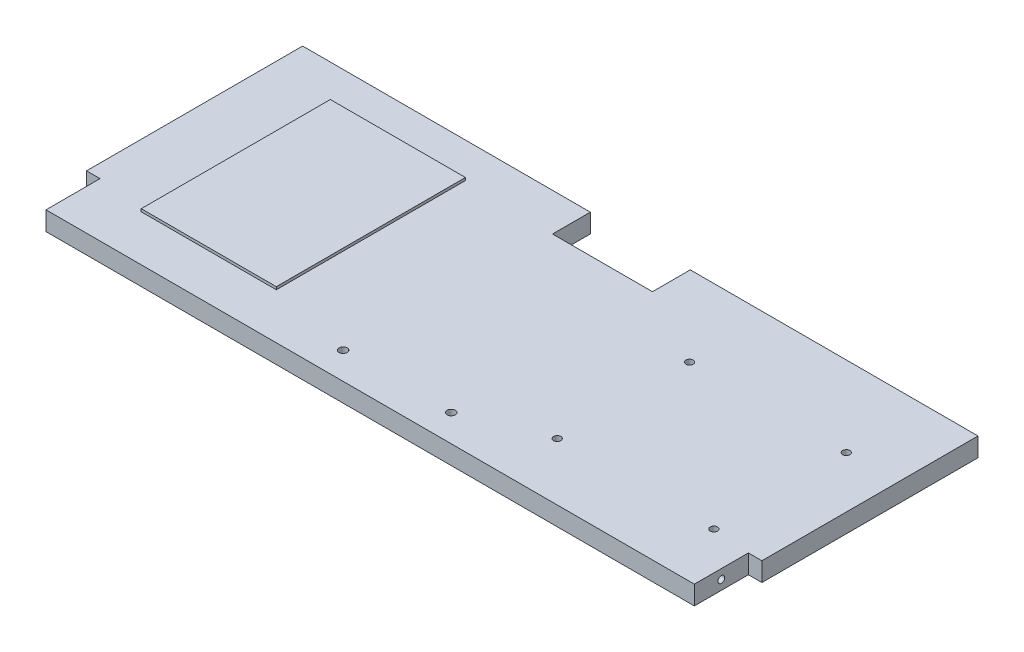
SolidWorks part; units mm, degrees
ref_plane "Ebene vorne" through (0, 0, 0) normal (0, 0, 1) x (1, 0, 0)
ref_plane "Ebene oben" through (0, 0, 0) normal (0, 1, 0) x (1, 0, 0)
ref_plane "Ebene rechts" through (0, 0, 0) normal (1, 0, 0) x (0, 0, -1)
sketch "Skizze1" plane through (0, 0, 0) normal (0, 1, 0) x (1, 0, 0)
  line L1 (-125, -125) -> (125, -125)
  line L2 (-125, -125) -> (-125, 125)
  line L3 (-125, 125) -> (125, 125)
  line L4 (125, -125) -> (125, 125)
  line L5 (-125, -125) -> (125, 125) construction
  line L6 (-125, 125) -> (125, -125) construction
  point P0 (0, 0)
  dimension "D1" = 250
  dimension "D2" = 250
extrude "Aufsatz-Linear austragen1" add sketch "Skizze1" along normal blind 5
sketch "Skizze2" plane through (0, 5, 0) normal (0, 1, 0) x (1, 0, 0)
  line L1 (-112.1275, -114.481) -> (-66.1275, -114.481)
  line L2 (-112.1275, -114.481) -> (-112.1275, -3.481)
  line L3 (-112.1275, -3.481) -> (-66.1275, -3.481)
  line L4 (-66.1275, -114.481) -> (-66.1275, -3.481)
  line L5 (-108.0153, 50.9925) -> (-23.0153, 50.9925)
  line L6 (-108.0153, 50.9925) -> (-108.0153, 110.9925)
  line L7 (-108.0153, 110.9925) -> (-23.0153, 110.9925)
  line L8 (-23.0153, 50.9925) -> (-23.0153, 110.9925)
  line L9 (-20, -105) -> (20, -105)
  line L10 (-20, -105) -> (-20, -65)
  line L11 (-20, -65) -> (20, -65)
  line L12 (20, -105) -> (20, -65)
  line L13 (65, -20) -> (105, -20)
  line L14 (65, -20) -> (65, 20)
  line L15 (65, 20) -> (105, 20)
  line L16 (105, -20) -> (105, 20)
  line L17 (6.7738, 50.9925) -> (91.7738, 50.9925)
  line L18 (6.7738, 50.9925) -> (6.7738, 110.9925)
  line L19 (6.7738, 110.9925) -> (91.7738, 110.9925)
  line L20 (91.7738, 50.9925) -> (91.7738, 110.9925)
  line L21 (-125, 125) -> (-125, -125) construction
  line L22 (-125, -125) -> (125, -125) construction
  line L23 (-100.1275, -122.481) -> (-100.1275, 4.519)
  line L24 (-120.1275, -122.481) -> (-58.1275, -122.481)
  line L25 (-120.1275, -122.481) -> (-120.1275, 4.519)
  line L26 (-120.1275, 4.519) -> (-58.1275, 4.519)
  line L27 (-58.1275, -122.481) -> (-58.1275, 4.519)
  line L28 (-78.1275, -122.481) -> (-78.1275, 4.519)
  line L29 (-120.1275, -92.481) -> (-57.4038, -92.481)
  line L30 (-120.1275, -25.481) -> (-58.1275, -25.481)
  circle A0 centre (0, 0) radius 1.65
  dimension "D1" = 3.3
  dimension "D2" = 46
  dimension "D3" = 111
  dimension "D4" = 40
  dimension "D5" = 40
  dimension "D6" = 60
  dimension "D7" = 85
  dimension "D8" = 40
  dimension "D9" = 40
  dimension "D10" = 65
  dimension "D11" = 125
  dimension "D12" = 125
  dimension "D13" = 65
  dimension "D14" = 105
  dimension "D15" = 105
  dimension "D16" = 8
  dimension "D17" = 8
  dimension "D18" = 8
  dimension "D19" = 8
  dimension "D20" = 30
  dimension "D21" = 30
  dimension "D22" = 20
  dimension "D23" = 20
extrude "Aufsatz-Linear austragen2" add sketch "Skizze2" along normal blind 15 contours L29 L25 L24 L23 L1 L2 | L29 L4 L1 L28 L24 L27 | L4 L30 L27 L26 L28 L3 | L25 L30 L2 L3 L23 L26 | L9 L12 L11 L10 | L13 L16 L15 L14
sketch "Skizze3" plane through (0, 20, 0) normal (0, 1, 0) x (1, 0, 0)
  line L0 (65, -20) -> (65, 20) construction
  line L1 (-20, -105) -> (20, -105)
  line L2 (-20, -105) -> (-20, -65)
  line L3 (-20, -65) -> (20, -65)
  line L4 (20, -105) -> (20, -65)
  line L5 (65, -20) -> (105, -20)
  line L6 (65, -20) -> (65, 20)
  line L7 (65, 20) -> (105, 20)
  line L8 (105, -20) -> (105, 20)
  line L9 (70, -15) -> (100, -15)
  line L10 (70, -15) -> (70, 15)
  line L11 (70, 15) -> (100, 15)
  line L12 (100, -15) -> (100, 15)
  line L13 (-15, -100) -> (15, -100)
  line L14 (-15, -100) -> (-15, -70)
  line L15 (-15, -70) -> (15, -70)
  line L16 (15, -100) -> (15, -70)
  circle A0 centre (0, 0) radius 1.65
  dimension "D9" = 3.3
  dimension "D1" = 5
  dimension "D2" = 5
  dimension "D3" = 5
  dimension "D4" = 5
  dimension "D5" = 5
  dimension "D6" = 5
  dimension "D7" = 5
  dimension "D8" = 5
extrude "Schnitt-Linear austragen1" cut sketch "Skizze3" against normal blind 15 contours L14 L13 L16 L15 | L10 L9 L12 L11 | A0
sketch "Skizze4" plane through (0, 5, 0) normal (0, 1, 0) x (1, 0, 0)
  line L1 (-15, -100) -> (15, -100)
  line L2 (-15, -100) -> (-15, -70)
  line L3 (-15, -70) -> (15, -70)
  line L4 (15, -100) -> (15, -70)
  line L5 (70, -15) -> (100, -15)
  line L6 (70, -15) -> (70, 15)
  line L7 (70, 15) -> (100, 15)
  line L8 (100, -15) -> (100, 15)
  circle A0 centre (0, 0) radius 1.65
  dimension "D1" = 3.3
extrude "Schnitt-Linear austragen2" cut sketch "Skizze4" against normal blind 15
sketch "Skizze6" plane through (0, 20, 0) normal (0, 1, 0) x (1, 0, 0)
  line L1 (-20, -105) -> (20, -105)
  line L2 (-20, -105) -> (-20, -65)
  line L3 (-20, -65) -> (20, -65)
  line L4 (20, -105) -> (20, -65)
  line L5 (65, -20) -> (105, -20)
  line L6 (65, -20) -> (65, 20)
  line L7 (65, 20) -> (105, 20)
  line L8 (105, -20) -> (105, 20)
extrude "Aufsatz-Linear austragen3" add sketch "Skizze6" against normal blind 5
sketch "Skizze7" plane through (0, 5, 0) normal (0, 1, 0) x (1, 0, 0)
  line L12 (-20, -105) -> (20, -105)
  line L13 (-20, -105) -> (-20, -65)
  line L14 (-20, -65) -> (20, -65)
  line L15 (20, -105) -> (20, -65)
  line L16 (65, -20) -> (105, -20)
  line L17 (65, -20) -> (65, 20)
  line L18 (65, 20) -> (105, 20)
  line L19 (105, -20) -> (105, 20)
extrude "Schnitt-Linear austragen3" cut sketch "Skizze7" along normal blind 43
sketch "Skizze8" plane through (0, 5, 0) normal (0, 1, 0) x (1, 0, 0)
  line L1 (-15, -100) -> (15, -100)
  line L2 (-15, -100) -> (-15, -70)
  line L3 (-15, -70) -> (15, -70)
  line L4 (15, -100) -> (15, -70)
  line L5 (70, -15) -> (100, -15)
  line L6 (70, -15) -> (70, 15)
  line L7 (70, 15) -> (100, 15)
  line L8 (100, -15) -> (100, 15)
extrude "Aufsatz-Linear austragen4" add sketch "Skizze8" against normal blind 5
sketch "Skizze9" plane through (0, 5, 0) normal (0, 1, 0) x (1, 0, 0)
  line L0 (0, -71) -> (0, -34.8212)
  line L1 (-6, -116) -> (39, -116)
  line L2 (-6, -116) -> (-6, -71)
  line L3 (-6, -71) -> (39, -71)
  line L4 (39, -116) -> (39, -71)
  line L5 (71, -39) -> (116, -39)
  line L6 (71, -39) -> (71, 6)
  line L7 (71, 6) -> (116, 6)
  line L8 (116, -39) -> (116, 6)
  line L9 (71, 0) -> (36.9303, 0)
  line L10 (125, 125) -> (-125, 125) construction
  line L11 (125, -125) -> (125, 125) construction
  dimension "D1" = 45
  dimension "D2" = 45
  dimension "D3" = 45
  dimension "D4" = 45
  dimension "D5" = 71
  dimension "D6" = 71
  dimension "D7" = 6
  dimension "D8" = 6
  dimension "D9" = 125
  dimension "D10" = 125
extrude "Aufsatz-Linear austragen5" add sketch "Skizze9" along normal blind 15 contours L1 L4 L3 L2 | L5 L8 L7 L6
sketch "Skizze10" plane through (0, 5, 0) normal (0, 1, 0) x (1, 0, 0)
  line L0 (-6, -116) -> (-6, -71) construction
  line L1 (-6, -93) -> (-14, -93)
  line L2 (-6, -93) -> (-6, -85)
  line L3 (-6, -85) -> (-14, -85)
  line L4 (-14, -93) -> (-14, -85)
  line L5 (39, -116) -> (39, -71) construction
  line L6 (39, -93) -> (47, -93)
  line L7 (39, -93) -> (39, -85)
  line L8 (39, -85) -> (47, -85)
  line L9 (47, -93) -> (47, -85)
  line L15 (71, 6) -> (116, 6) construction
  line L16 (93, 6) -> (85, 6)
  line L17 (93, 6) -> (93, 14)
  line L18 (93, 14) -> (85, 14)
  line L19 (85, 6) -> (85, 14)
  line L22 (71, -39) -> (71, 6) construction
  line L23 (85, -39) -> (93, -39)
  line L24 (85, -39) -> (85, -47)
  line L25 (85, -47) -> (93, -47)
  line L26 (93, -39) -> (93, -47)
  line L27 (-6, -71) -> (39, -71) construction
  line L28 (-6, -71) -> (39, -71) construction
  dimension "D1" = 8
  dimension "D2" = 8
  dimension "D3" = 14
  dimension "D4" = 8
  dimension "D5" = 8
  dimension "D7" = 8
  dimension "D8" = 14
  dimension "D9" = 8
  dimension "D10" = 14
  dimension "D11" = 14
  dimension "D12" = 8
  dimension "D13" = 8
extrude "Aufsatz-Linear austragen6" add sketch "Skizze10" along normal blind 34 contours L7 L6 L9 L8 | L2 L1 L4 L3 | L24 L23 L26 L25 | L17 L16 L19 L18
sketch "Skizze11" plane through (0, 0, 85) normal (0, 0, -1) x (-1, 0, 0)
  line L0 (-47, 39) -> (-47, 5) construction
  line L1 (14, 39) -> (6, 39)
  line L2 (14, 39) -> (14, 20)
  line L3 (14, 20) -> (6, 20)
  line L4 (6, 39) -> (6, 20)
  line L5 (-39, 39) -> (-47, 39)
  line L6 (-39, 39) -> (-39, 20)
  line L7 (-39, 20) -> (-47, 20)
  line L8 (-47, 39) -> (-47, 20)
  line L9 (10.85, 31.9) -> (10.85, 26.5)
  line L10 (-43.85, 31.9) -> (-43.85, 26.5)
  circle A0 centre (10.85, 34.05) radius 2.15
  circle A1 centre (10.85, 24.35) radius 2.15
  circle A2 centre (-43.85, 34.05) radius 2.15
  circle A3 centre (-43.85, 24.35) radius 2.15
  dimension "D1" = 4.3
  dimension "D2" = 4.3
  dimension "D3" = 4.3
  dimension "D4" = 4.3
  dimension "D5" = 5.4
  dimension "D6" = 3.15
  dimension "D7" = 5.4
  dimension "D8" = 3.15
  dimension "D9" = 4.35
  dimension "D10" = 4.35
extrude "Schnitt-Linear austragen4" cut sketch "Skizze11" against normal blind 34 contours A0 | A1 | A2 | A3
sketch "Skizze12" plane through (0, 5, 0) normal (0, 1, 0) x (1, 0, 0)
  line L0 (71, 0) -> (57, 0)
  line L1 (71, -39) -> (71, 6) construction
  line L2 (125, 125) -> (-125, 125) construction
  line L3 (125, -125) -> (125, 125) construction
  line L4 (0, 0) -> (0, -71)
  line L6 (-6, -71) -> (39, -71) construction
  line L10 (-22.6064, -118.7348) -> (120.4564, -118.7348)
  line L11 (-22.6064, -118.7348) -> (-22.6064, 65.7516)
  line L12 (-22.6064, 65.7516) -> (120.4564, 65.7516)
  line L13 (120.4564, -118.7348) -> (120.4564, 65.7516)
  dimension "D1" = 14
  dimension "D2" = 125
  dimension "D3" = 68
  dimension "D4" = 57
  dimension "D5" = 71
extrude "Schnitt-Linear austragen5" cut sketch "Skizze12" along normal blind 60
sketch "Skizze13" plane through (0, 5, 0) normal (0, 1, 0) x (1, 0, 0)
  line L0 (0, -74) -> (0, -63)
  line L1 (-6, -119) -> (39, -119)
  line L2 (-6, -119) -> (-6, -74)
  line L3 (-6, -74) -> (39, -74)
  line L4 (39, -119) -> (39, -74)
  line L5 (74, -39) -> (119, -39)
  line L6 (74, -39) -> (74, 6)
  line L7 (74, 6) -> (119, 6)
  line L8 (119, -39) -> (119, 6)
  line L9 (74, 0) -> (63, 0)
  line L10 (-125, 125) -> (-125, -125) construction
  line L11 (-125, -125) -> (125, -125) construction
  dimension "D1" = 6
  dimension "D2" = 6
  dimension "D3" = 125
  dimension "D4" = 125
  dimension "D5" = 11
  dimension "D6" = 11
  dimension "D7" = 63
  dimension "D8" = 45
  dimension "D9" = 45
  dimension "D10" = 63
  dimension "D11" = 45
  dimension "D12" = 45
extrude "Aufsatz-Linear austragen7" add sketch "Skizze13" along normal blind 15 contours L1 L4 L3 L2 | L5 L8 L7 L6
sketch "Skizze14" plane through (0, 5, 0) normal (0, 1, 0) x (1, 0, 0)
  line L0 (-6, -119) -> (-6, -74) construction
  line L1 (-6, -95) -> (-14, -95)
  line L2 (-6, -95) -> (-6, -87)
  line L3 (-6, -87) -> (-14, -87)
  line L4 (-14, -95) -> (-14, -87)
  line L5 (39, -119) -> (39, -74) construction
  line L6 (39, -95) -> (47, -95)
  line L7 (39, -95) -> (39, -87)
  line L8 (39, -87) -> (47, -87)
  line L9 (47, -95) -> (47, -87)
  line L10 (74, -39) -> (119, -39) construction
  line L11 (87, -39) -> (95, -39)
  line L12 (87, -39) -> (87, -47)
  line L13 (87, -47) -> (95, -47)
  line L14 (95, -39) -> (95, -47)
  line L15 (74, 6) -> (119, 6) construction
  line L16 (95, 6) -> (87, 6)
  line L17 (95, 6) -> (95, 14)
  line L18 (95, 14) -> (87, 14)
  line L19 (87, 6) -> (87, 14)
  line L20 (74, -39) -> (74, 6) construction
  line L21 (74, -39) -> (74, 6) construction
  line L22 (-6, -74) -> (39, -74) construction
  line L23 (-6, -74) -> (39, -74) construction
  dimension "D1" = 8
  dimension "D2" = 8
  dimension "D3" = 8
  dimension "D4" = 8
  dimension "D5" = 8
  dimension "D6" = 8
  dimension "D7" = 8
  dimension "D8" = 8
  dimension "D9" = 13
  dimension "D10" = 13
  dimension "D11" = 13
  dimension "D12" = 13
extrude "Aufsatz-Linear austragen8" add sketch "Skizze14" along normal blind 34
sketch "Skizze15" plane through (0, 5, 0) normal (0, 1, 0) x (1, 0, 0)
  line L0 (125, 125) -> (-125, 125) construction
  line L1 (-18.5, 111) -> (18.5, 111)
  line L2 (-18.5, 111) -> (-18.5, 125)
  line L3 (-18.5, 125) -> (18.5, 125)
  line L4 (18.5, 111) -> (18.5, 125)
  line L5 (-125, 125) -> (-125, -125) construction
  dimension "D1" = 14
  dimension "D2" = 37
  dimension "D3" = 106.5
extrude "Schnitt-Linear austragen6" cut sketch "Skizze15" against normal blind 10 contours L2 L1 L4 L3
sketch "Skizze16" plane through (0, 5, 0) normal (0, 1, 0) x (1, 0, 0)
  line L1 (-101.7331, 41.9857) -> (-51.7331, 41.9857)
  line L2 (-101.7331, 41.9857) -> (-101.7331, 111.9857)
  line L3 (-101.7331, 111.9857) -> (-51.7331, 111.9857)
  line L4 (-51.7331, 41.9857) -> (-51.7331, 111.9857)
  line L5 (27.6532, 40.8623) -> (112.6532, 40.8623)
  line L6 (27.6532, 40.8623) -> (27.6532, 96.6623)
  line L7 (27.6532, 96.6623) -> (112.6532, 96.6623)
  line L8 (112.6532, 40.8623) -> (112.6532, 96.6623)
  dimension "D1" = 70
  dimension "D2" = 50
  dimension "D3" = 85
  dimension "D4" = 55.8
extrude "Aufsatz-Linear austragen9" add sketch "Skizze16" along normal blind 1 contours L2 L1 L4 L3
sketch "Skizze17" plane through (0, 5, 0) normal (0, 1, 0) x (1, 0, 0)
  line L1 (24.3018, 42.8865) -> (109.3018, 42.8865)
  line L2 (24.3018, 42.8865) -> (24.3018, 98.6865)
  line L3 (24.3018, 98.6865) -> (109.3018, 98.6865)
  line L4 (109.3018, 42.8865) -> (109.3018, 98.6865)
  circle A0 centre (105.9518, 46.2865) radius 1.35
  circle A1 centre (105.9518, 95.2865) radius 1.35
  circle A2 centre (47.9518, 46.2865) radius 1.35
  circle A3 centre (47.9518, 95.2865) radius 1.35
  dimension "D3" = 2.7
  dimension "D4" = 2.7
  dimension "D5" = 2.7
  dimension "D6" = 2.7
  dimension "D1" = 85
  dimension "D2" = 55.8
  dimension "D7" = 49
  dimension "D8" = 3.4
  dimension "D9" = 49
  dimension "D10" = 3.4
  dimension "D11" = 58
  dimension "D12" = 58
  dimension "D13" = 3.35
  dimension "D14" = 3.35
extrude "Schnitt-Linear austragen7" cut sketch "Skizze17" against normal blind 21 contours A2 | A3 | A1 | A0
sketch "Skizze18" plane through (0, 0, 87) normal (0, 0, -1) x (-1, 0, 0)
  line L0 (10.85, 31.9) -> (10.85, 26.5)
  line L1 (14, 39) -> (6, 39)
  line L2 (14, 39) -> (14, 20)
  line L3 (14, 20) -> (6, 20)
  line L4 (6, 39) -> (6, 20)
  line L5 (-43.85, 31.9) -> (-43.85, 26.5)
  line L6 (-39, 39) -> (-47, 39)
  line L7 (-39, 39) -> (-39, 20)
  line L8 (-39, 20) -> (-47, 20)
  line L9 (-47, 39) -> (-47, 20)
  line L10 (-47, 39) -> (-47, 5) construction
  circle A0 centre (10.85, 34.05) radius 2.15
  circle A1 centre (10.85, 24.35) radius 2.15
  circle A2 centre (-43.85, 34.05) radius 2.15
  circle A3 centre (-43.85, 24.35) radius 2.15
  dimension "D1" = 4.3
  dimension "D2" = 4.3
  dimension "D6" = 4.3
  dimension "D7" = 4.3
  dimension "D3" = 5.4
  dimension "D4" = 4.35
  dimension "D5" = 3.15
  dimension "D8" = 4.35
  dimension "D9" = 5.4
  dimension "D10" = 3.15
extrude "Schnitt-Linear austragen8" cut sketch "Skizze18" against normal blind 21 contours A0 | A1 | A2 | A3
sketch "Skizze19" plane through (87, 0, 0) normal (-1, 0, 0) x (0, 0, 1)
  line L0 (43.85, 31.9) -> (43.85, 26.5)
  line L1 (47, 39) -> (39, 39)
  line L2 (47, 39) -> (47, 20)
  line L3 (47, 20) -> (39, 20)
  line L4 (39, 39) -> (39, 20)
  line L5 (-10.85, 31.9) -> (-10.85, 26.5)
  line L6 (-6, 39) -> (-14, 39)
  line L7 (-6, 39) -> (-6, 20)
  line L8 (-6, 20) -> (-14, 20)
  line L9 (-14, 39) -> (-14, 20)
  line L10 (-14, 39) -> (-14, 5) construction
  circle A0 centre (43.85, 34.05) radius 2.15
  circle A1 centre (43.85, 24.35) radius 2.15
  circle A2 centre (-10.85, 34.05) radius 2.15
  circle A3 centre (-10.85, 24.35) radius 2.15
  dimension "D1" = 4.3
  dimension "D2" = 4.3
  dimension "D6" = 4.3
  dimension "D7" = 4.3
  dimension "D3" = 5.4
  dimension "D4" = 4.35
  dimension "D5" = 3.15
  dimension "D8" = 5.4
  dimension "D9" = 4.35
  dimension "D10" = 3.15
extrude "Schnitt-Linear austragen9" cut sketch "Skizze19" against normal blind 21 contours A0 | A1 | A2 | A3
sketch "Skizze20" plane through (0, 5, 0) normal (0, 1, 0) x (1, 0, 0)
  line L0 (-125, 125) -> (-125, -125) construction
  line L1 (125, -125) -> (-125, -125)
  line L2 (125, -125) -> (125, 25)
  line L3 (125, 25) -> (-125, 25)
  line L4 (-125, -125) -> (-125, 25)
  dimension "D1" = 150
extrude "Schnitt-Linear austragen10" cut sketch "Skizze20" along normal blind 35 and the other way blind 36
sketch "Skizze21" plane through (0, 5, 0) normal (0, 1, 0) x (1, 0, 0)
  line L1 (125, 25) -> (120, 25)
  line L2 (125, 25) -> (125, 45)
  line L3 (125, 45) -> (120, 45)
  line L4 (120, 25) -> (120, 45)
  line L5 (-125, 25) -> (-120, 25)
  line L6 (-125, 25) -> (-125, 45)
  line L7 (-125, 45) -> (-120, 45)
  line L8 (-120, 25) -> (-120, 45)
  dimension "D1" = 20
  dimension "D2" = 5
  dimension "D3" = 5
  dimension "D4" = 20
extrude "Schnitt-Linear austragen11" cut sketch "Skizze21" against normal blind 10 contours L6 L5 L8 L7 | L2 L1 L4 L3
sketch "Skizze22" plane through (-120, 0, 0) normal (-1, 0, 0) x (0, 0, 1)
  line L0 (-25, 5) -> (-45, 5)
  line L1 (-25, 5) -> (-45, 5)
  line L2 (-25, 5) -> (-25, 0)
  line L3 (-25, 0) -> (-45, 0)
  line L4 (-45, 5) -> (-45, 0)
  line L5 (-25, 5) -> (-25, 0)
  line L6 (-25, 0) -> (-45, 0)
  line L7 (-45, 5) -> (-45, 0)
  circle A1 centre (-35, 1.5) radius 1.25
  dimension "D4" = 2.5
  dimension "D5" = 1.5
  dimension "D6" = 10
extrude "Schnitt-Linear austragen13" cut sketch "Skizze22" against normal blind 20 contours A1
sketch "Skizze25" plane through (120, 0, 0) normal (1, 0, 0) x (0, 0, -1)
  line L0 (45, 5) -> (25, 5)
  line L1 (45, 5) -> (45, 0)
  line L2 (45, 0) -> (25, 0)
  line L3 (25, 5) -> (25, 0)
  circle A0 centre (35, 1.5) radius 1.25
  dimension "D1" = 2.5
  dimension "D2" = 1.5
  dimension "D3" = 10
extrude "Schnitt-Linear austragen14" cut sketch "Skizze25" against normal blind 20 contours A0
sketch "Skizze26" plane through (0, 5, 0) normal (0, 1, 0) x (1, 0, 0)
  line L0 (-120, 25) -> (120, 25) construction
  line L1 (-30, 25) -> (30, 25)
  line L2 (-30, 25) -> (-30, 45)
  line L3 (-30, 45) -> (30, 45)
  line L4 (30, 25) -> (30, 45)
  line L5 (-120, 25) -> (-120, 45) construction
  circle A0 centre (-20, 35) radius 1.5
  circle A1 centre (20, 35) radius 1.5
  dimension "D6" = 3
  dimension "D7" = 3
  dimension "D1" = 60
  dimension "D2" = 20
  dimension "D3" = 90
  dimension "D4" = 10
  dimension "D5" = 10
  dimension "D8" = 10
  dimension "D9" = 10
extrude "Schnitt-Linear austragen15" cut sketch "Skizze26" against normal blind 10 contours A0 | A1
sketch "Skizze28" plane through (0, 0, 0) normal (0, -1, 0) x (-1, 0, 0)
  line L1 (-125, 45) -> (125, 45)
  line L2 (-125, 45) -> (-125, 125)
  line L3 (-125, 125) -> (125, 125)
  line L4 (125, 45) -> (125, 125)
  line L5 (-18.5, 111) -> (18.5, 111)
  line L6 (-18.5, 111) -> (-18.5, 125)
  line L7 (-18.5, 125) -> (18.5, 125)
  line L8 (18.5, 111) -> (18.5, 125)
  line L9 (-120, 25) -> (120, 25)
  line L10 (-120, 25) -> (-120, 45)
  line L11 (-120, 45) -> (120, 45)
  line L12 (120, 25) -> (120, 45)
  circle A0 centre (20, 35) radius 1.5
  circle A1 centre (-20, 35) radius 1.5
  circle A2 centre (-47.9518, 46.2865) radius 1.35
  circle A3 centre (-47.9518, 95.2865) radius 1.35
  circle A4 centre (-105.9518, 46.2865) radius 1.35
  circle A5 centre (-105.9518, 95.2865) radius 1.35
  circle M5 centre (20, 35) radius 1.5
  circle M6 centre (-20, 35) radius 1.5
  circle M7 centre (-105.9518, 46.2865) radius 1.35
  circle M8 centre (-105.9518, 95.2865) radius 1.35
  circle M9 centre (-47.9518, 95.2865) radius 1.35
  circle M10 centre (-47.9518, 46.2865) radius 1.35
  line M11 (120, 25) -> (120, 45)
  line M12 (120, 45) -> (125, 45)
  line M13 (125, 45) -> (125, 125)
  line M14 (125, 125) -> (18.5, 125)
  line M15 (18.5, 125) -> (18.5, 111)
  line M16 (18.5, 111) -> (-18.5, 111)
  line M17 (-18.5, 111) -> (-18.5, 125)
  line M18 (-18.5, 125) -> (-125, 125)
  line M19 (-125, 125) -> (-125, 45)
  line M20 (-125, 45) -> (-120, 45)
  line M21 (-120, 45) -> (-120, 25)
  line M22 (-120, 25) -> (120, 25)
extrude "Aufsatz-Linear austragen10" add sketch "Skizze28" along normal blind 2 contours L1 M20 M7 M10 M12 M13 M14 M15 M16 M17 M18 M19 M9 M8 | L1 M21 M22 M11 M10 M7 M6 M5
